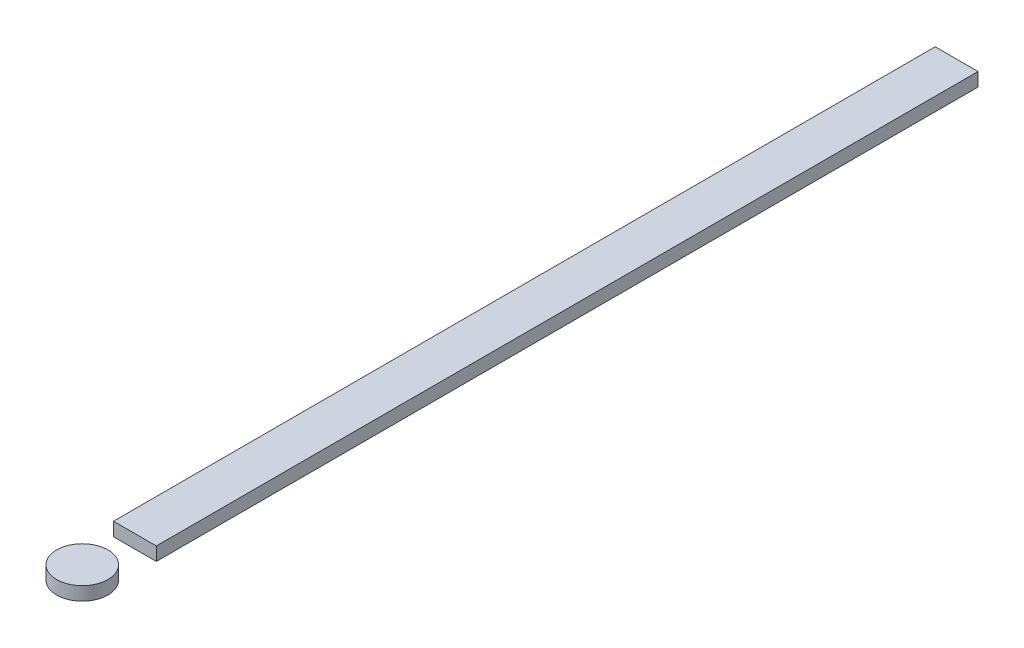
SolidWorks part; units mm, degrees
ref_plane "Front Plane" through (0, 0, 0) normal (0, 0, 1) x (1, 0, 0)
ref_plane "Top Plane" through (0, 0, 0) normal (0, 1, 0) x (1, 0, 0)
ref_plane "Right Plane" through (0, 0, 0) normal (1, 0, 0) x (0, 0, -1)
sketch "Sketch1" plane through (0, 0, 0) normal (0, 1, 0) x (1, 0, 0)
  circle A0 centre (0, 0) radius 1.905
  dimension "D1" = 3.81
extrude "Boss-Extrude1" add sketch "Sketch1" along normal blind 1
sketch "Sketch2" plane through (0, 0, 0) normal (0, 1, 0) x (1, 0, 0)
  line L1 (-1.6357, 3.9519) -> (1.5393, 3.9519)
  line L2 (-1.6357, 3.9519) -> (-1.6357, 64.9119)
  line L3 (-1.6357, 64.9119) -> (1.5393, 64.9119)
  line L4 (1.5393, 3.9519) -> (1.5393, 64.9119)
  dimension "D1" = 60.96
  dimension "D2" = 3.175
extrude "Boss-Extrude2" add sketch "Sketch2" along normal blind 1 separate body
